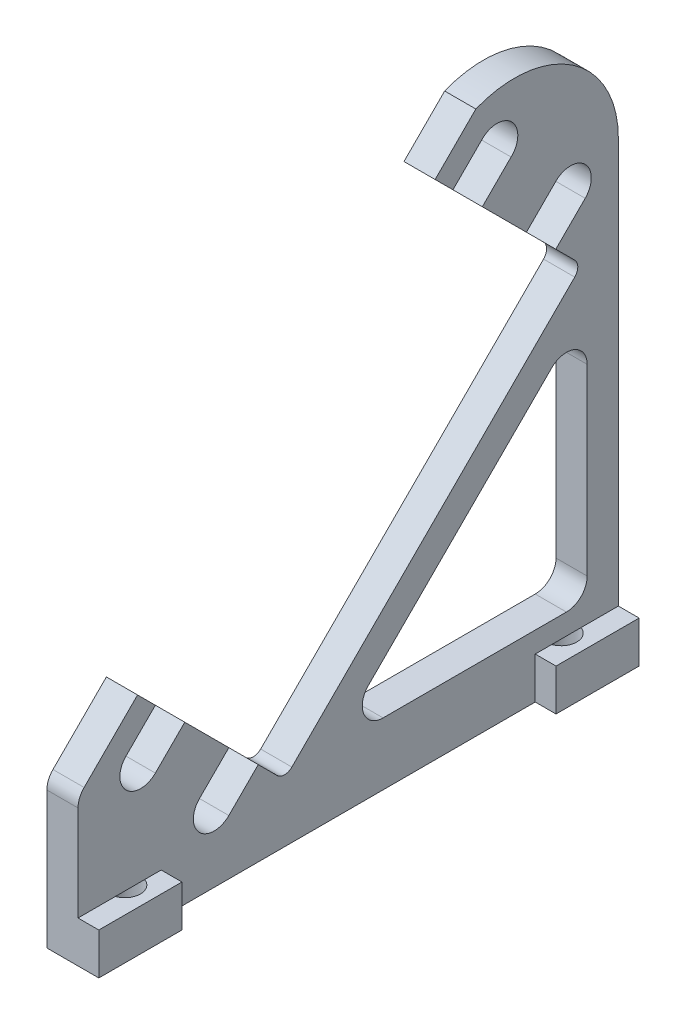
SolidWorks part; units mm, degrees
ref_plane "前视基准面" through (0, 0, 0) normal (0, 0, 1) x (1, 0, 0)
ref_plane "上视基准面" through (0, 0, 0) normal (0, 1, 0) x (1, 0, 0)
ref_plane "右视基准面" through (0, 0, 0) normal (1, 0, 0) x (0, 0, -1)
sketch "草图1" plane through (0, 0, 0) normal (1, 0, 0) x (0, 0, -1)
  line L0 (0, 0) -> (0, 43)
  line L1 (0, 0) -> (-52, 0)
  line L2 (-52, 0) -> (-52, 13.1716)
  line L3 (-51.4142, 14.5858) -> (-46.2716, 19.7284)
  line L4 (-13.0906, 49.48) -> (-15.919, 46.6515)
  line L5 (-10.2004, 46.7161) -> (-13.0919, 43.8244)
  line L6 (-6.0195, 42.4089) -> (-8.848, 39.5805)
  line L7 (-3.1911, 39.5805) -> (-6.0195, 36.752)
  line L8 (-30.2379, 32.3326) -> (-20.3384, 22.4331) construction
  line L9 (-17.6337, 48.3663) -> (-15.919, 46.6515)
  line L10 (-46.2716, 19.7284) -> (-44.5569, 18.0137)
  line L11 (-31.4223, 6.2934) -> (-4.1987, 33.517)
  line L12 (-17.6337, 48.3663) -> (-13.7161, 52.2839)
  line L13 (-44.5569, 18.0137) -> (-47.3853, 15.1853)
  line L14 (-41.7285, 15.1854) -> (-44.5568, 12.3569)
  line L15 (-37.4858, 10.9426) -> (-40.3142, 8.1142)
  line L16 (-34.6574, 8.1142) -> (-37.4858, 5.2858)
  line L17 (-41.7285, 15.1854) -> (-37.4858, 10.9426)
  line L18 (-34.6574, 8.1142) -> (-32.8365, 6.2934)
  line L19 (-13.0919, 43.8244) -> (-8.848, 39.5805)
  line L20 (-6.0195, 36.752) -> (-4.1987, 34.9312)
  line L21 (-6.4142, 27.0589) -> (-24.0589, 9.4142)
  line L22 (-22.6447, 6) -> (-5, 6)
  line L23 (-3, 8) -> (-3, 25.6447)
  arc A0 (-4.1987, 33.517) -> (-4.1987, 34.9312) centre (-4.9058, 34.2241) ccw
  arc A1 (-40.3142, 8.1142) -> (-37.4858, 5.2858) centre (-38.9, 6.7) ccw
  arc A2 (-47.3853, 15.1853) -> (-44.5568, 12.3569) centre (-45.9711, 13.7711) ccw
  arc A3 (-10.3266, 46.5899) -> (-13.0906, 49.48) centre (-11.6764, 48.0657) ccw
  arc A4 (-3.1911, 39.5805) -> (-6.0195, 42.4089) centre (-4.6053, 40.9947) ccw
  arc A5 (0, 43) -> (-13.7161, 52.2839) centre (-10, 43) ccw
  arc A6 (-32.8365, 6.2934) -> (-31.4223, 6.2934) centre (-32.1294, 7.0005) ccw
  arc A7 (-52, 13.1716) -> (-51.4142, 14.5858) centre (-50, 13.1716) cw
  arc A8 (-5, 6) -> (-3, 8) centre (-5, 8) ccw
  arc A9 (-22.6447, 6) -> (-24.0589, 9.4142) centre (-22.6447, 8) cw
  arc A10 (-3, 25.6447) -> (-6.4142, 27.0589) centre (-5, 25.6447) ccw
  point P17 (-3.4916, 34.2241)
  point P39 (-32.1294, 5.5863)
  point P42 (-52, 14)
  dimension "D3" = 20
  dimension "D8" = 4
  dimension "D10" = 4
  dimension "D13" = 1
  dimension "D14" = 2
  dimension "D18" = 2
  dimension "D1" = 43
  dimension "D2" = 52
  dimension "D4" = 14
  dimension "D5" = 45
  dimension "D6" = 6.7
  dimension "D7" = 13.1
  dimension "D9" = 2
  dimension "D11" = 10
  dimension "D12" = 20.25
  dimension "D15" = 3
  dimension "D16" = 3
  dimension "D17" = 6
  dimension "D19" = 48.5
extrude "凸台-拉伸1" add sketch "草图1" along normal blind 5 contours A7 L2 L1 L0 A5 L12 L9 L4 A3 L5 L19 L6 A4 L7 L20 A0 L11 A6 L18 L16 A1 L15 L17 L14 A2 L13 L10 L3 A10 L23 A8 L22 A9 L21
sketch "草图2" plane through (5, 0, 0) normal (1, 0, 0) x (0, 0, -1)
  line L0 (9.2864, 4) -> (-8, 4)
  line L1 (-8, 4) -> (-8, -3.7323)
  line L2 (-8, -3.7323) -> (-44, -3.7323)
  line L3 (-44, -3.7323) -> (-44, 4)
  line L4 (-44, 4) -> (-56.6225, 4)
  line L5 (-56.6225, 4) -> (-56.6225, 58.4945)
  line L6 (-56.6225, 58.4945) -> (9.2864, 58.4945)
  line L7 (9.2864, 58.4945) -> (9.2864, 4)
  line L8 (0, 0) -> (-52, 0) construction
  line L9 (-52, 0) -> (-52, 13.1716) construction
  line L10 (0, 0) -> (0, 43) construction
  dimension "D1" = 4
  dimension "D2" = 4
  dimension "D3" = 8
  dimension "D4" = 8
extrude "切除-拉伸1" cut sketch "草图2" against normal blind 2
sketch "草图3" plane through (0, 0, 0) normal (0, -1, 0) x (1, 0, 0)
  line L0 (2.5, 52) -> (2.5, 0) construction
  line L1 (5, 52) -> (0, 52) construction
  line L2 (5, 0) -> (0, 0) construction
  circle A0 centre (2.5, 47) radius 1.5
  circle A1 centre (2.5, 5) radius 1.5
  dimension "D1" = 3
  dimension "D2" = 3
  dimension "D3" = 5
  dimension "D4" = 5
extrude "切除-拉伸2" cut sketch "草图3" against normal blind 4
